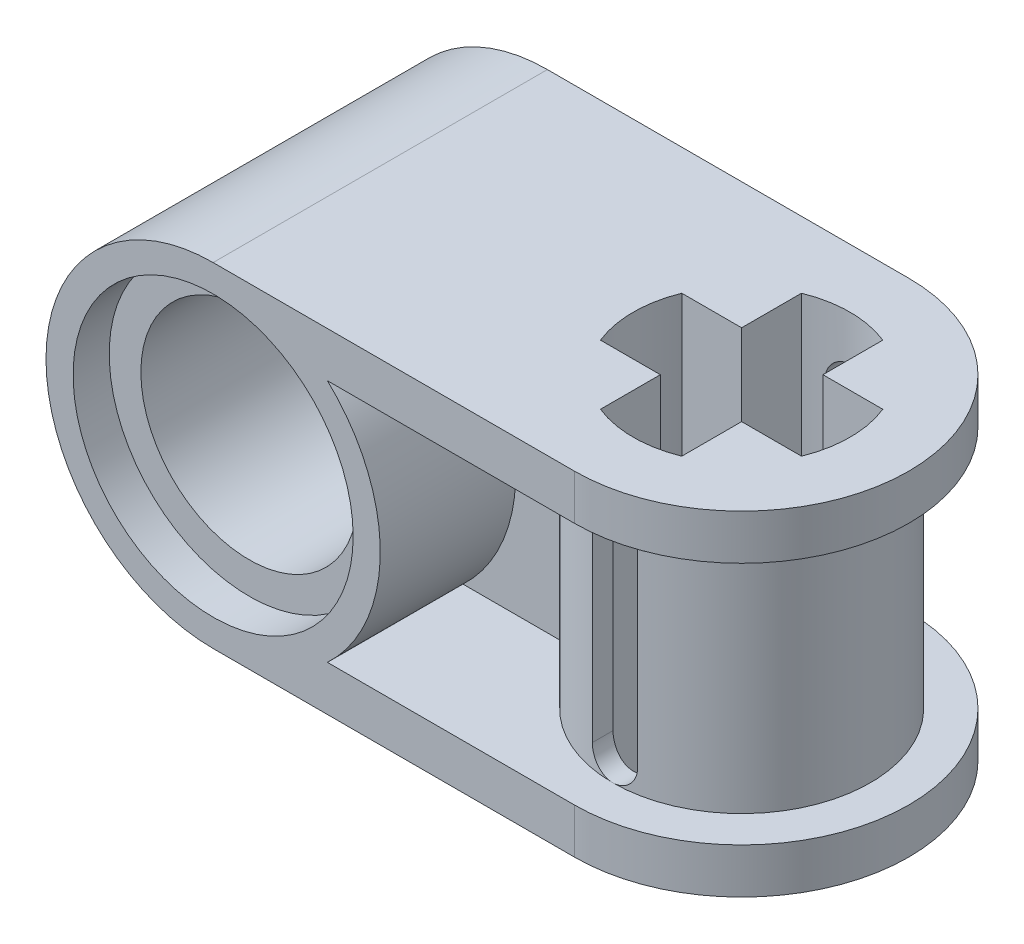
SolidWorks part; units mm, degrees
ref_plane "Front Plane" through (0, 0, 0) normal (0, 0, 1) x (1, 0, 0)
ref_plane "Top Plane" through (0, 0, 0) normal (0, 1, 0) x (1, 0, 0)
ref_plane "Right Plane" through (0, 0, 0) normal (1, 0, 0) x (0, 0, -1)
sketch "Sketch1" plane through (0, 0, 0) normal (0, 0, 1) x (1, 0, 0)
  circle A0 centre (0, 0) radius 3.7
  circle A1 centre (0, 0) radius 2.4
  dimension "D1" = 7.4
  dimension "D2" = 4.8
extrude "Pin Side" add sketch "Sketch1" along normal mid plane 7.4
sketch "Sketch2" plane through (0, 0, 0) normal (0, 1, 0) x (1, 0, 0)
  line L7 (0, 3.7) -> (0, -3.7)
  line L8 (3.7, 3.7) -> (-3.7, 3.7) construction
  line L9 (-3.7, -3.7) -> (3.7, -3.7) construction
  line L10 (0, -3.7) -> (8, -3.7)
  line L11 (0, 3.7) -> (8, 3.7)
  line L12 (-3.7, 3.7) -> (-3.7, -3.7) construction
  arc A0 (8, 3.7) -> (8, -3.7) centre (8, 0) cw
  dimension "D1" = 15.4
extrude "Side Ear" add sketch "Sketch2" against normal blind 1 from offset 3.7
mirror "Mirror1" about plane through (0, 0, 0) normal (0, 1, 0) of "Side Ear"
sketch "Sketch3" plane through (0, 0, 0) normal (0, 0, 1) x (1, 0, 0)
  line L0 (2.5298, -2.7) -> (8, -2.7) construction
  line L1 (2.5298, 2.7) -> (8, 2.7) construction
  line L2 (2.5298, -2.7) -> (8, -2.7)
  line L3 (2.5298, 2.7) -> (8, 2.7)
  line L4 (8, 2.7) -> (8, -2.7)
  arc A0 (2.5298, -2.7) -> (2.5298, 2.7) centre (0, 0) ccw construction
  arc A1 (2.5298, -2.7) -> (2.5298, 2.7) centre (0, 0) ccw
extrude "Middle Rib" add sketch "Sketch3" along normal mid plane 1.4
sketch "Sketch4" plane through (0, 0, 0) normal (0, 1, 0) x (1, 0, 0)
  circle A0 centre (8, 0) radius 2.85
  dimension "D1" = 5.7
extrude "Axle Body" add sketch "Sketch4" along normal mid plane 7.4
sketch "Sketch5" plane through (0, 0, 0) normal (0, 1, 0) x (1, 0, 0)
  line L1 (8.9, -2.4) -> (7.1, -2.4)
  line L2 (8.9, -2.4) -> (8.9, 2.4)
  line L3 (8.9, 2.4) -> (7.1, 2.4)
  line L4 (7.1, -2.4) -> (7.1, 2.4)
  line L5 (8.9, -2.4) -> (7.1, 2.4) construction
  line L6 (8.9, 2.4) -> (7.1, -2.4) construction
  line L7 (10.4, -0.9) -> (5.6, -0.9)
  line L8 (10.4, -0.9) -> (10.4, 0.9)
  line L9 (10.4, 0.9) -> (5.6, 0.9)
  line L10 (5.6, -0.9) -> (5.6, 0.9)
  line L11 (10.4, -0.9) -> (5.6, 0.9) construction
  line L12 (10.4, 0.9) -> (5.6, -0.9) construction
  circle A0 centre (8, 0) radius 2.4
  dimension "D1" = 4.8
  dimension "D2" = 1.8
extrude "Axle Cut " cut sketch "Sketch5" against normal through all both and the other way through all contours L9 A0 L7 L4 | L2 A0 L4 L9 | L2 L9 L4 L7 | L7 A0 L9 L2 | A0 L2 L7 L4
sketch "Sketch6" plane through (0, 0, 0) normal (0, 0, 1) x (1, 0, 0)
  line L0 (8, -2.2) -> (8, 2.2) construction
  line L1 (7.5, -2.2) -> (7.5, 2.2)
  line L2 (8.5, -2.2) -> (8.5, 2.2)
  line L3 (8, 2.7) -> (8, 3.7) construction
  line L4 (5.2373, 2.7) -> (10.85, 2.7) construction
  arc A0 (7.5, -2.2) -> (8.5, -2.2) centre (8, -2.2) ccw
  arc A1 (8.5, 2.2) -> (7.5, 2.2) centre (8, 2.2) ccw
  point P2 (8, 0)
  point P7 (0, 0)
  dimension "D1" = 1
extrude "Axle Slot " cut sketch "Sketch6" against normal through all both and the other way through all
sketch "Sketch7" plane through (0, 0, 3.7) normal (0, 0, 1) x (1, 0, 0)
  circle A0 centre (0, 0) radius 3.1
  dimension "D1" = 6.2
extrude "Pin Rim" cut sketch "Sketch7" against normal blind 0.8
mirror "Mirror2" about plane through (0, 0, 0) normal (0, 0, 1) of "Pin Rim"
